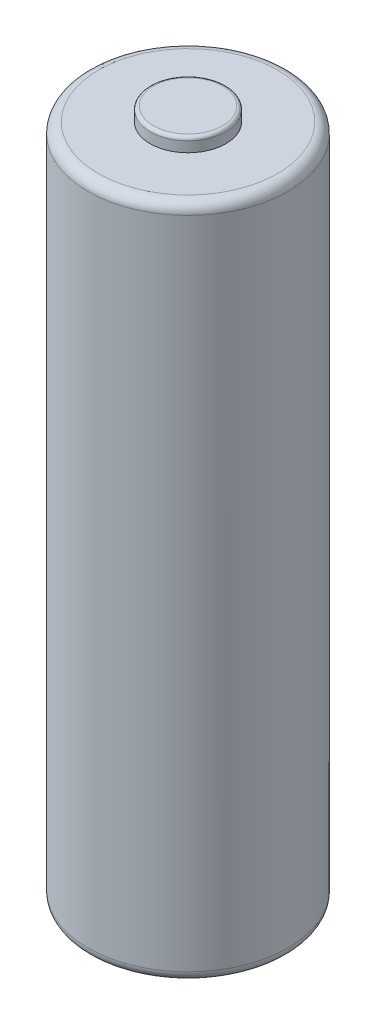
SolidWorks part; units mm, degrees
ref_plane "Front Plane" through (0, 0, 0) normal (0, 0, 1) x (1, 0, 0)
ref_plane "Top Plane" through (0, 0, 0) normal (0, 1, 0) x (1, 0, 0)
ref_plane "Right Plane" through (0, 0, 0) normal (1, 0, 0) x (0, 0, -1)
sketch "Sketch1" plane through (0, 0, 0) normal (0, 0, 1) x (1, 0, 0)
  line L0 (0, 0) -> (0, -53.4264) construction
  line L1 (0, 0) -> (-7.25, 0)
  line L2 (-7.25, 0) -> (-7.25, -49)
  line L4 (0, -49.5) -> (0, 0)
  line L5 (0, -49.5) -> (-3.5, -49.5)
  line L6 (-3.5, -49.5) -> (-6.3356, -49)
  line L7 (-6.3356, -49) -> (-7.25, -49)
  dimension "D1" = 14.5
  dimension "D2" = 0.5
  dimension "D3" = 49.5
  dimension "D4" = 7
  dimension "D5" = 10
revolve "Revolve1" add sketch "Sketch1" angle 360 about L0
sketch "Sketch2" plane through (0, 0, 0) normal (0, 0, 1) x (1, 0, 0)
  line L0 (0, 0) -> (0, 11.638) construction
  line L1 (7.25, 0) -> (-7.25, 0) construction
  line L2 (0, 1) -> (-2.75, 1)
  line L3 (-2.75, 1) -> (-2.75, 0)
  line L4 (-2.75, 0) -> (0, 0)
  line L5 (0, 0) -> (0, 1)
  dimension "D1" = 5.5
  dimension "D2" = 1
revolve "Revolve2" add sketch "Sketch2" angle 360 about L0
fillet "Fillet1" radius 0.75 2 edges at (0, 0, 7.25) (0, -49, 7.25)
fillet "Fillet2" radius 0.25 1 edges at (0, 1, -2.75)
